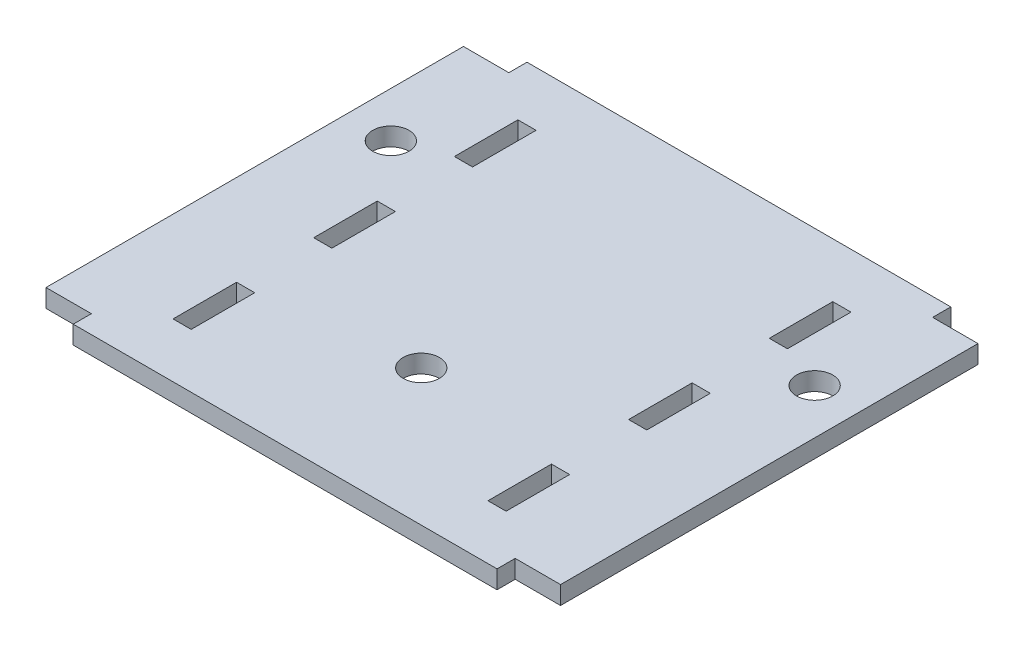
SolidWorks part; units mm, degrees
ref_plane "Front Plane" through (0, 0, 0) normal (0, 0, 1) x (1, 0, 0)
ref_plane "Top Plane" through (0, 0, 0) normal (0, 1, 0) x (1, 0, 0)
ref_plane "Right Plane" through (0, 0, 0) normal (1, 0, 0) x (0, 0, -1)
sketch "Sketch1" plane through (0, 0, 0) normal (0, 1, 0) x (1, 0, 0)
  line L0 (-35.6495, -41.9807) -> (-37.6495, -41.9807)
  line L1 (-70.7995, 2.0193) -> (32.2005, 2.0193)
  line L2 (-70.7995, 2.0193) -> (-70.7995, -47.9807)
  line L3 (-70.7995, -47.9807) -> (32.2005, -47.9807)
  line L4 (32.2005, 2.0193) -> (32.2005, -47.9807)
  line L5 (-35.6495, -41.9807) -> (-35.6495, -34.9807)
  line L6 (-35.6495, -34.9807) -> (-37.6495, -34.9807)
  line L7 (-37.6495, -41.9807) -> (-37.6495, -34.9807)
  line L8 (-35.6495, -26.4807) -> (-37.6495, -26.4807)
  line L9 (-35.6495, -26.4807) -> (-35.6495, -19.4807)
  line L10 (-35.6495, -19.4807) -> (-37.6495, -19.4807)
  line L11 (-37.6495, -26.4807) -> (-37.6495, -19.4807)
  line L12 (-35.6495, -10.9807) -> (-37.6495, -10.9807)
  line L13 (-35.6495, -10.9807) -> (-35.6495, -3.9807)
  line L14 (-35.6495, -3.9807) -> (-37.6495, -3.9807)
  line L15 (-37.6495, -10.9807) -> (-37.6495, -3.9807)
  line L16 (-0.9495, -10.9807) -> (-2.9495, -10.9807)
  line L17 (-0.9495, -10.9807) -> (-0.9495, -3.9807)
  line L18 (-0.9495, -3.9807) -> (-2.9495, -3.9807)
  line L19 (-2.9495, -10.9807) -> (-2.9495, -3.9807)
  line L20 (-0.9495, -26.4807) -> (-2.9495, -26.4807)
  line L21 (-0.9495, -26.4807) -> (-0.9495, -19.4807)
  line L22 (-0.9495, -19.4807) -> (-2.9495, -19.4807)
  line L23 (-2.9495, -26.4807) -> (-2.9495, -19.4807)
  line L24 (-0.9495, -41.9807) -> (-2.9495, -41.9807)
  line L25 (-0.9495, -41.9807) -> (-0.9495, -34.9807)
  line L26 (-0.9495, -34.9807) -> (-2.9495, -34.9807)
  line L27 (-2.9495, -41.9807) -> (-2.9495, -34.9807)
  line L29 (-47.6495, -47.9807) -> (-42.6495, -47.9807)
  line L30 (-47.6495, -47.9807) -> (-47.6495, -45.9807)
  line L31 (-47.6495, -45.9807) -> (-42.6495, -45.9807)
  line L32 (-42.6495, -47.9807) -> (-42.6495, -45.9807)
  line L33 (4.0505, -47.9807) -> (9.0505, -47.9807)
  line L34 (4.0505, -47.9807) -> (4.0505, -45.9807)
  line L35 (4.0505, -45.9807) -> (9.0505, -45.9807)
  line L36 (9.0505, -47.9807) -> (9.0505, -45.9807)
  line L37 (-47.6495, 2.0193) -> (-42.6495, 2.0193)
  line L38 (-47.6495, 2.0193) -> (-47.6495, 0.0193)
  line L39 (-47.6495, 0.0193) -> (-42.6495, 0.0193)
  line L40 (-42.6495, 2.0193) -> (-42.6495, 0.0193)
  line L41 (4.0505, 2.0193) -> (9.0505, 2.0193)
  line L42 (4.0505, 2.0193) -> (4.0505, 0.0193)
  line L43 (4.0505, 0.0193) -> (9.0505, 0.0193)
  line L44 (9.0505, 2.0193) -> (9.0505, 0.0193)
  circle A0 centre (-42.6495, -12.9807) radius 2
  circle A1 centre (4.0505, -12.9807) radius 2
  circle A2 centre (-19.2995, -32.9807) radius 2
  dimension "D21" = 4
  dimension "D22" = 4
  dimension "D24" = 32.7
  dimension "D25" = 32.7
  dimension "D27" = 15
  dimension "D29" = 4
  dimension "D31" = 51.5
  dimension "D1" = 50
  dimension "D2" = 103
  dimension "D4" = 7
  dimension "D5" = 2
  dimension "D6" = 7
  dimension "D7" = 2
  dimension "D8" = 7
  dimension "D9" = 2
  dimension "D10" = 7
  dimension "D11" = 2
  dimension "D12" = 7
  dimension "D13" = 2
  dimension "D14" = 7
  dimension "D15" = 2
  dimension "D16" = 8.5
  dimension "D17" = 8.5
  dimension "D18" = 8.5
  dimension "D19" = 8.5
  dimension "D20" = 32.7
  dimension "D23" = 0
  dimension "D26" = 0
  dimension "D28" = 15
  dimension "D30" = 35
  dimension "D32" = 0
  dimension "D33" = 0
  dimension "D34" = 0
  dimension "D35" = 6
  dimension "D36" = 6
  dimension "D37" = 6
  dimension "D38" = 6
  dimension "D39" = 33.15
  dimension "D40" = 33.15
  dimension "D41" = 16.35
  dimension "D42" = 16.35
  dimension "D43" = 2
  dimension "D44" = 5
  dimension "D45" = 5
  dimension "D46" = 2
  dimension "D47" = 5
  dimension "D48" = 5
  dimension "D49" = 5
  dimension "D50" = 5
  dimension "D51" = 2
  dimension "D52" = 5
  dimension "D53" = 5
  dimension "D54" = 2
  dimension "D55" = 35
extrude "Boss-Extrude1" add sketch "Sketch1" along normal blind 2 contours L1 L44 L43 L42 L40 L39 L38 L2 L3 L30 L31 L32 L34 L35 L36 L4 A2 A1 A0 L0 L7 L6 L5 L8 L11 L10 L9 L12 L15 L14 L13 L16 L19 L18 L17 L20 L23 L22 L21
sketch "Sketch2" plane through (0, 0, 0) normal (0, -1, 0) x (-1, 0, 0)
  line L1 (70.7995, -47.9807) -> (47.6495, -47.9807)
  line L2 (70.7995, -47.9807) -> (70.7995, 2.0193)
  line L3 (70.7995, 2.0193) -> (47.6495, 2.0193)
  line L4 (47.6495, -47.9807) -> (47.6495, 2.0193)
  line L5 (-32.2005, -47.9807) -> (-9.0505, -47.9807)
  line L6 (-32.2005, -47.9807) -> (-32.2005, 2.0193)
  line L7 (-32.2005, 2.0193) -> (-9.0505, 2.0193)
  line L8 (-9.0505, -47.9807) -> (-9.0505, 2.0193)
extrude "Cut-Extrude1" cut sketch "Sketch2" against normal blind 10
